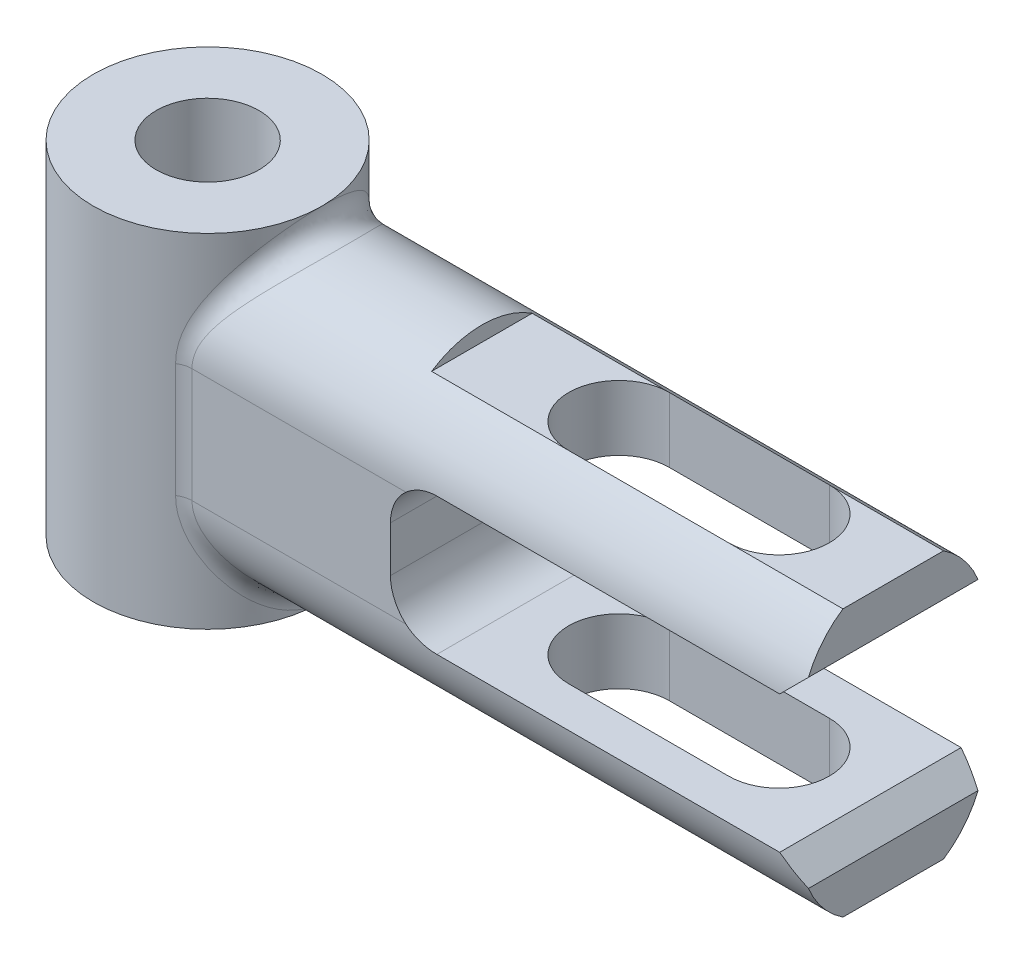
SolidWorks part; units mm, degrees
ref_plane "Front Plane" through (0, 0, 0) normal (0, 0, 1) x (1, 0, 0)
ref_plane "Top Plane" through (0, 0, 0) normal (0, 1, 0) x (1, 0, 0)
ref_plane "Right Plane" through (0, 0, 0) normal (1, 0, 0) x (0, 0, -1)
sketch "Sketch2" plane through (0, 0, 0) normal (0, 1, 0) x (1, 0, 0)
  circle A0 centre (0, 0) radius 5
  dimension "D1" = 10
extrude "Boss-Extrude1" add sketch "Sketch2" along normal blind 15
sketch "Sketch3" plane through (0, 0, 0) normal (1, 0, 0) x (0, 0, -1)
  line L1 (0, 5) -> (0, 10) construction
  line L2 (-4, 5) -> (-4, 10)
  line L3 (4, 5) -> (4, 10)
  arc A1 (-4, 5) -> (4, 5) centre (0, 5) ccw
  arc A2 (4, 10) -> (-4, 10) centre (0, 10) ccw
  point P2 (0, 7.5)
  dimension "D1" = 5
  dimension "D2" = 8
  dimension "D3" = 7.5
extrude "Boss-Extrude2" add sketch "Sketch3" along normal blind 30
sketch "Sketch5" plane through (0, 0, 0) normal (0, 1, 0) x (1, 0, 0)
  line L0 (18, 0) -> (25, 0) construction
  line L1 (18, 2.2) -> (25, 2.2)
  line L2 (18, -2.2) -> (25, -2.2)
  arc A0 (18, 2.2) -> (18, -2.2) centre (18, 0) ccw
  arc A1 (25, -2.2) -> (25, 2.2) centre (25, 0) ccw
  point P3 (21.5, 0)
  dimension "D1" = 25
  dimension "D2" = 18
  dimension "D3" = 4.4
extrude "Cut-Extrude1" cut sketch "Sketch5" along normal through all
hole_wizard "M4 Clearance Hole1" positions "Sketch6" profile "Sketch7" hole size "M4" standard "ANSI Metric" end condition through all
sketch "Sketch6" plane through (0, 15, 0) normal (0, 1, 0) x (1, 0, 0)
  point P0 (0, 0)
sketch "Sketch7" plane through (0, 15, 0) normal (1, 0, 0) x (0, 0, 1)
  line L0 (0, 0) -> (0, 15)
  line L1 (0, 15) -> (2.25, 15)
  line L2 (2.25, 15) -> (2.25, 0)
  line L5 (2.25, 0) -> (0, 0)
  line L11 (0, -6.35) -> (0, 107.95) construction
  dimension "Thru Hole Dia." = 4.5
  dimension "Thru Hole Depth" = 15
fillet "Fillet1" radius 1 4 edges at (4.9827, 1.0216, 0.4154) (3, 7.5, 4) (4.9827, 6.0216, 0.4154) (3, 7.5, -4)
sketch "Sketch8" plane through (0, 0, 4) normal (0, 0, 1) x (1, 0, 0)
  line L1 (30, 10.5) -> (12, 10.5)
  line L2 (30, 10.5) -> (30, 4.5)
  line L3 (30, 4.5) -> (12, 4.5)
  line L4 (12, 10.5) -> (12, 4.5)
  line L5 (30, 10) -> (3.3166, 10) construction
  line L8 (30, 5) -> (3.3166, 5) construction
  line L9 (30, 10) -> (30, 5) construction
  line L10 (12, 1) -> (12, 1.6593)
  line L11 (5.9999, 1) -> (15.8, 1) construction
  line L12 (12, 1.6593) -> (30, 1.6593)
  line L13 (30, 1) -> (30, 5) construction
  line L14 (25, 1.6593) -> (18, 1.6593) construction
  line L15 (12, 1) -> (30, 1)
  line L16 (30, 1) -> (30, 1.6593)
  line L17 (30, 7.5) -> (32.4519, 7.5) construction
  line L18 (30, 14) -> (30, 13.3407)
  line L19 (12, 14) -> (30, 14)
  line L20 (12, 13.3407) -> (30, 13.3407)
  line L21 (12, 14) -> (12, 13.3407)
  dimension "D1" = 18
  dimension "D2" = 0.5
  dimension "D3" = 0.5
extrude "Cut-Extrude2" cut sketch "Sketch8" against normal through all
chamfer "Chamfer1" distance 1 angle 45 2 edges at (30, 4.5, 0) (30, 10.5, 0)
fillet "Fillet2" radius 2 2 edges at (12, 10.5, 0) (12, 4.5, 0)
